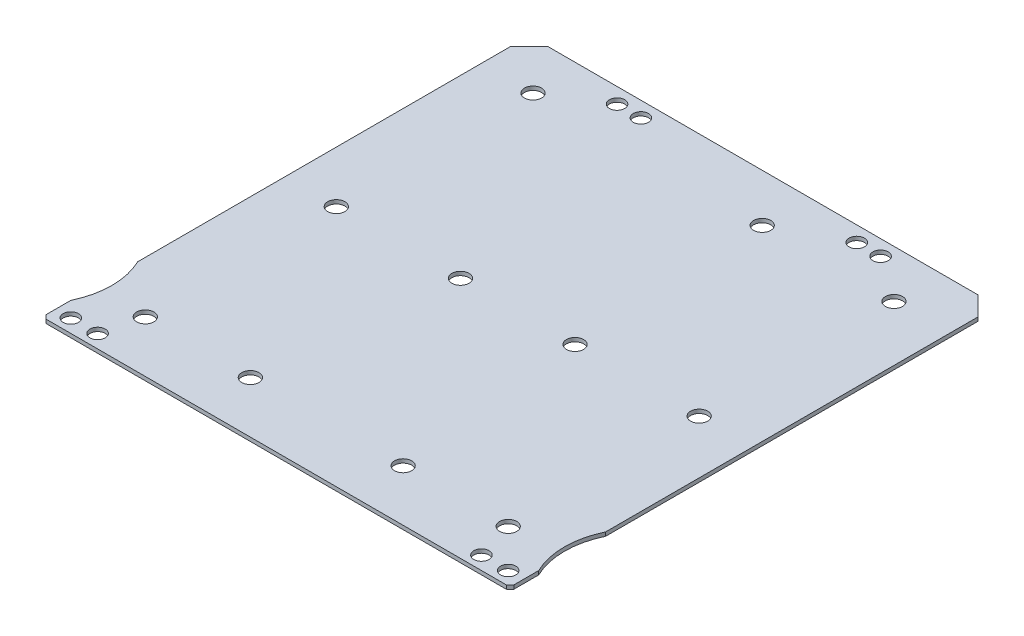
SolidWorks part; units mm, degrees
ref_plane "Front Plane" through (0, 0, 0) normal (0, 0, 1) x (1, 0, 0)
ref_plane "Top Plane" through (0, 0, 0) normal (0, 1, 0) x (1, 0, 0)
ref_plane "Right Plane" through (0, 0, 0) normal (1, 0, 0) x (0, 0, -1)
sketch "Sketch1" plane through (0, 0, 0) normal (0, 1, 0) x (1, 0, 0)
  line L0 (0, 127) -> (245, 127) construction
  line L1 (0, 0) -> (245, 0)
  line L2 (0, 50) -> (0, 255)
  line L3 (0, 255) -> (245, 255)
  line L4 (245, 0) -> (245, 15)
  line L5 (0, 247) -> (245, 247) construction
  line L6 (0, 230) -> (245, 230) construction
  line L7 (0, 27) -> (245, 27) construction
  line L8 (0, 7) -> (245, 7) construction
  line L9 (0, 0) -> (0, 15) construction
  line L10 (0, 15) -> (4, 15) construction
  line L11 (4, 15) -> (4, 50) construction
  line L12 (4, 50) -> (0, 50) construction
  line L13 (122.5, 255) -> (122.5, 0) construction
  line L14 (245, 50) -> (245, 255)
  line L15 (0, 0) -> (0, 15)
  circle A0 centre (8, 7) radius 4
  circle A1 centre (22, 7) radius 4
  circle A2 centre (237, 7) radius 4
  circle A3 centre (223, 7) radius 4
  circle A4 centre (27, 27) radius 4.5
  circle A5 centre (82, 27) radius 4.5
  circle A6 centre (162, 27) radius 4.5
  circle A7 centre (217, 27) radius 4.5
  circle A8 centre (27, 127) radius 4.5
  circle A9 centre (92, 127) radius 4.5
  circle A10 centre (152, 127) radius 4.5
  circle A11 centre (217, 127) radius 4.5
  circle A12 centre (27, 230) radius 4.5
  circle A13 centre (147, 230) radius 4.5
  circle A14 centre (216, 230) radius 4.5
  circle A15 centre (54, 247) radius 4
  circle A16 centre (66.5, 247) radius 4
  circle A17 centre (179.5, 247) radius 4
  circle A18 centre (192, 247) radius 4
  arc A19 (0, 50) -> (0, 15) centre (-36.2813, 32.5) cw
  arc A20 (245, 50) -> (245, 15) centre (281.2813, 32.5) ccw
  dimension "D8" = 8
  dimension "D12" = 27
  dimension "D16" = 65
  dimension "D20" = 27
  dimension "D1" = 245
  dimension "D2" = 255
  dimension "D3" = 7
  dimension "D4" = 27
  dimension "D5" = 127
  dimension "D6" = 230
  dimension "D7" = 247
  dimension "D9" = 14
  dimension "D10" = 201
  dimension "D11" = 14
  dimension "D13" = 55
  dimension "D14" = 80
  dimension "D15" = 55
  dimension "D17" = 65
  dimension "D18" = 60
  dimension "D19" = 27
  dimension "D21" = 120
  dimension "D22" = 69
  dimension "D23" = 54
  dimension "D24" = 12.5
  dimension "D25" = 12.5
  dimension "D26" = 113
  dimension "D27" = 4
  dimension "D28" = 15
  dimension "D29" = 35
extrude "Boss-Extrude1" add sketch "Sketch1" along normal blind 2
chamfer "Chamfer1" distance 2 angle 45 2 edges at (0, 1, 0) (245, 1, 0)
chamfer "Chamfer2" distance 10 angle 45 2 edges at (245, 1, -255) (0, 1, -255)
